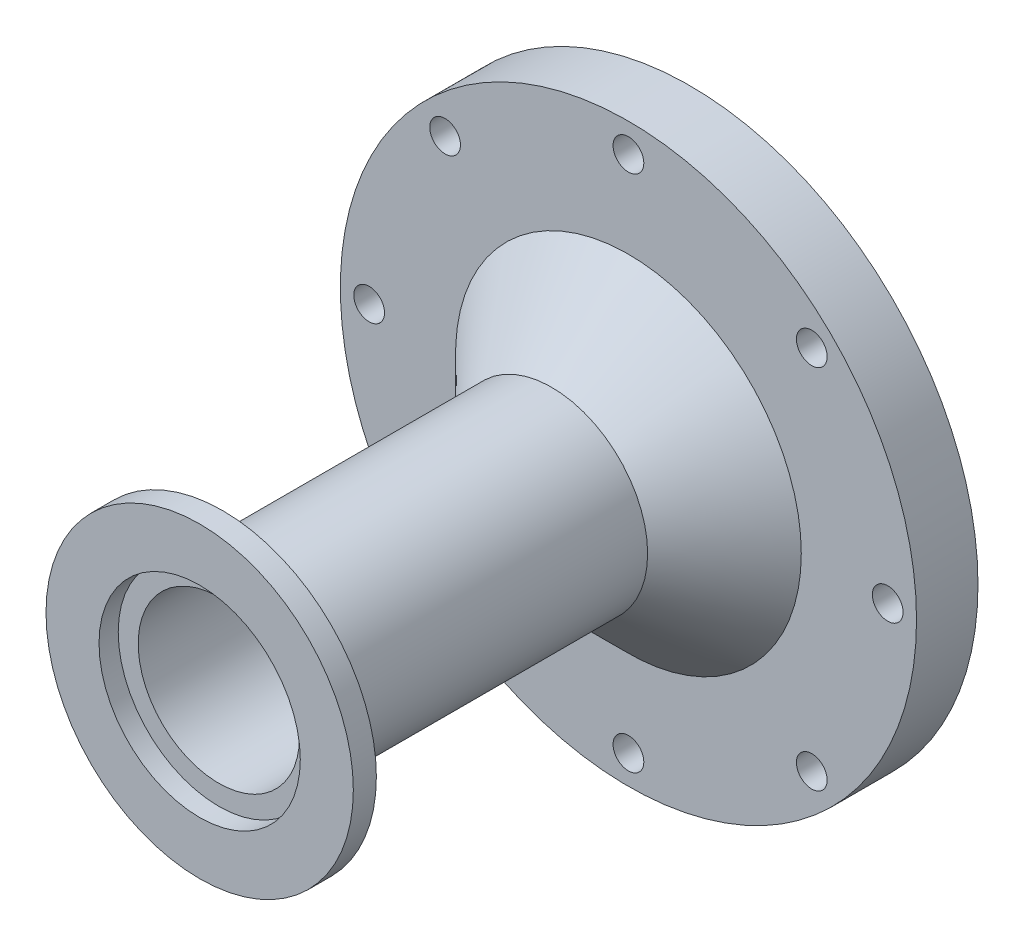
SolidWorks part; units mm, degrees
material "AISI 316 Stainless Steel Sheet (SS)"
ref_plane "Front Plane" through (0, 0, 0) normal (0, 0, 1) x (1, 0, 0)
ref_plane "Top Plane" through (0, 0, 0) normal (0, 1, 0) x (1, 0, 0)
ref_plane "Right Plane" through (0, 0, 0) normal (1, 0, 0) x (0, 0, -1)
sketch "Sketch1" plane through (0, 0, 0) normal (0, 0, 1) x (1, 0, 0)
  circle A0 centre (0, 0) radius 20.71 construction
  circle A1 centre (0, 0) radius 20.71
  circle A2 centre (0, 0) radius 19.21 construction
  circle A3 centre (0, 0) radius 19.21
  circle A5 centre (0, 0) radius 37.5 construction
  circle A6 centre (23.8649, -23.8649) radius 2 construction
  circle A7 centre (33.75, 0) radius 2 construction
  circle A8 centre (-23.8649, 23.8649) radius 2 construction
  circle A9 centre (-33.75, 0) radius 2 construction
  circle A10 centre (-23.8649, -23.8649) radius 2 construction
  circle A11 centre (0, -33.75) radius 2 construction
  circle A12 centre (23.8649, -23.8649) radius 2
  circle A13 centre (33.75, 0) radius 2
  circle A14 centre (-23.8649, 23.8649) radius 2
  circle A15 centre (-33.75, 0) radius 2
  circle A16 centre (-23.8649, -23.8649) radius 2
  circle A17 centre (0, -33.75) radius 2
  circle A18 centre (0, 0) radius 37.5
sketch "Sketch2" plane through (0, 0, 0) normal (0, 0, 1) x (1, 0, 0)
  circle A1 centre (0, 0) radius 37.5 construction
  circle A2 centre (0, 0) radius 5.35 construction
  circle A3 centre (0, 0) radius 5.35
  circle A4 centre (0, 0) radius 37.5
extrude "Boss-Extrude2" add sketch "Sketch2" along normal blind 8
sketch "Sketch3" plane through (0, 0, 0) normal (0, 0, 1) x (1, 0, 0)
  circle A0 centre (0, 0) radius 20.71 construction
  circle A1 centre (0, 0) radius 20.71
  circle A2 centre (0, 0) radius 19.21 construction
  circle A3 centre (0, 0) radius 19.21
sketch "Sketch14" plane through (0, 0, 0) normal (0, 0, 1) x (1, 0, 0)
  circle A7 centre (0, 33.75) radius 2
  circle A8 centre (0, 33.75) radius 2
  circle A9 centre (-23.8649, 23.8649) radius 2
  circle A10 centre (-23.8649, 23.8649) radius 2
  circle A11 centre (-33.75, 0) radius 2
  circle A12 centre (-33.75, 0) radius 2
  circle A13 centre (-23.8649, -23.8649) radius 2
  circle A14 centre (-23.8649, -23.8649) radius 2
  circle A15 centre (0, -33.75) radius 2
  circle A16 centre (0, -33.75) radius 2
  circle A17 centre (23.8649, -23.8649) radius 2
  circle A18 centre (23.8649, -23.8649) radius 2
  circle A19 centre (33.75, 0) radius 2
  circle A20 centre (33.75, 0) radius 2
  circle A21 centre (23.8649, 23.8649) radius 2
  circle A22 centre (23.8649, 23.8649) radius 2
  dimension "D1" = 0
  dimension "D2" = 0
  dimension "D3" = 0
  dimension "D4" = 0
  dimension "D5" = 0
  dimension "D6" = 0
  dimension "D7" = 0
  dimension "D8" = 0
extrude "Cut-Extrude6" cut sketch "Sketch14" along normal through all
extrude "Cut-Extrude2" cut sketch "Sketch3" along normal blind 2
sketch "Sketch6" plane through (0, 0, 8) normal (0, 0, 1) x (1, 0, 0)
  circle A1 centre (0, 0) radius 10.45
  circle A2 centre (0, 0) radius 5.35 construction
  circle A3 centre (0, 0) radius 6.45
  dimension "D1" = 1.1
  dimension "D2" = 4
extrude "Boss-Extrude3" [suppressed] add sketch "Sketch6" along normal blind 40
sketch "Sketch7" plane through (0, 0, 8) normal (0, 0, 1) x (1, 0, 0)
  circle A0 centre (0, 0) radius 12.5
  circle A1 centre (0, 0) radius 10.5
  dimension "D1" = 25
  dimension "D2" = 2
extrude "Boss-Extrude4" add sketch "Sketch7" along normal blind 50.8
sketch "Sketch10" plane through (0, 0, 58.8) normal (0, 0, 1) x (1, 0, 0)
  circle A0 centre (0, 0) radius 12.5 construction
  circle A1 centre (0, 0) radius 12.5
extrude "Boss-Extrude5" add sketch "Sketch10" along normal blind 2.01 draft 75 draft outward yes
sketch "Sketch11" plane through (0, 0, 60.81) normal (0, 0, 1) x (1, 0, 0)
  circle A1 centre (0, 0) radius 10.5 construction
  circle A2 centre (0, 0) radius 10.5
extrude "Cut-Extrude3" cut sketch "Sketch11" against normal through all
sketch "Sketch12" plane through (0, 0, 60.81) normal (0, 0, 1) x (1, 0, 0)
  circle A0 centre (0, 0) radius 10.5 construction
  circle A1 centre (0, 0) radius 20.0014 construction
  circle A2 centre (0, 0) radius 10.5
  circle A3 centre (0, 0) radius 20.0014
extrude "Boss-Extrude6" add sketch "Sketch12" along normal blind 3
sketch "Sketch13" plane through (0, 0, 63.81) normal (0, 0, 1) x (1, 0, 0)
  circle A0 centre (0, 0) radius 13.1
  dimension "D1" = 26.2
extrude "Cut-Extrude4" cut sketch "Sketch13" against normal blind 2.5
chamfer "Chamfer1" distance 10 angle 45 1 edges at (12.5, 0, 8)
chamfer "Chamfer2" [suppressed] distance 10 angle 45
sketch "Sketch15" [suppressed] plane through (0, 0, 48) normal (0, 0, 1) x (1, 0, 0)
  circle A2 centre (0, 0) radius 7.35
  circle A3 centre (0, 0) radius 7.35
  dimension "D1" = 2
extrude "Cut-Extrude7" [suppressed] cut sketch "Sketch15" against normal blind 10
